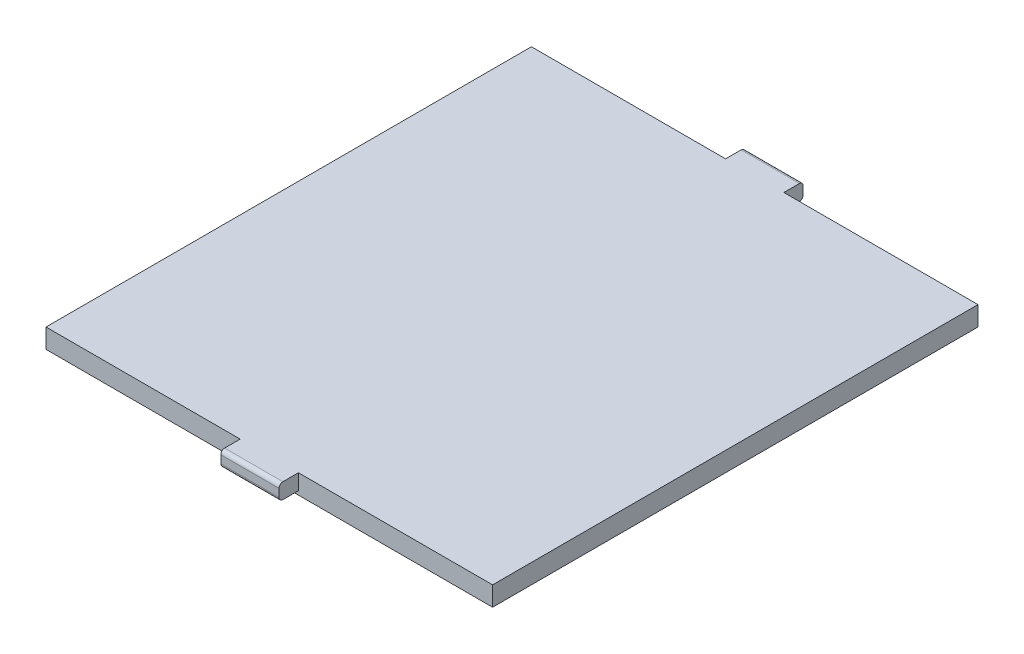
SolidWorks part; units mm, degrees
ref_plane "Front Plane" through (0, 0, 0) normal (0, 0, 1) x (1, 0, 0)
ref_plane "Top Plane" through (0, 0, 0) normal (0, 1, 0) x (1, 0, 0)
ref_plane "Right Plane" through (0, 0, 0) normal (1, 0, 0) x (0, 0, -1)
sketch "Sketch1" plane through (0, 0, 0) normal (0, 1, 0) x (1, 0, 0)
  line L1 (0, 0) -> (584.2, 0)
  line L2 (0, 0) -> (0, 635)
  line L3 (0, 635) -> (584.2, 635)
  line L4 (584.2, 0) -> (584.2, 635)
extrude "Boss-Extrude1" add sketch "Sketch1" along normal blind 25.4
sketch "Sketch2" plane through (0, 0, 0) normal (0, 0, 1) x (1, 0, 0)
  line L0 (0, 25.4) -> (584.2, 25.4) construction
  line L1 (254, 25.4) -> (330.2, 25.4)
  line L2 (254, 25.4) -> (254, 5.08)
  line L3 (254, 5.08) -> (330.2, 5.08)
  line L4 (330.2, 25.4) -> (330.2, 5.08)
extrude "Boss-Extrude2" add sketch "Sketch2" along normal blind 25.4
sketch "Sketch3" plane through (0, 0, -635) normal (0, 0, -1) x (-1, 0, 0)
  line L0 (-584.2, 25.4) -> (0, 25.4) construction
  line L1 (-330.2, 25.4) -> (-254, 25.4)
  line L2 (-330.2, 25.4) -> (-330.2, 5.08)
  line L3 (-330.2, 5.08) -> (-254, 5.08)
  line L4 (-254, 25.4) -> (-254, 5.08)
extrude "Boss-Extrude3" add sketch "Sketch3" along normal blind 25.4
fillet "Fillet1" radius 5.08 1 edges at (292.1, 25.4, -660.4)
fillet "Fillet2" radius 5.08 1 edges at (292.1, 5.08, -660.4)
fillet "Fillet3" radius 5.08 1 edges at (292.1, 5.08, 25.4)
fillet "Fillet4" radius 5.08 1 edges at (292.1, 25.4, 25.4)
